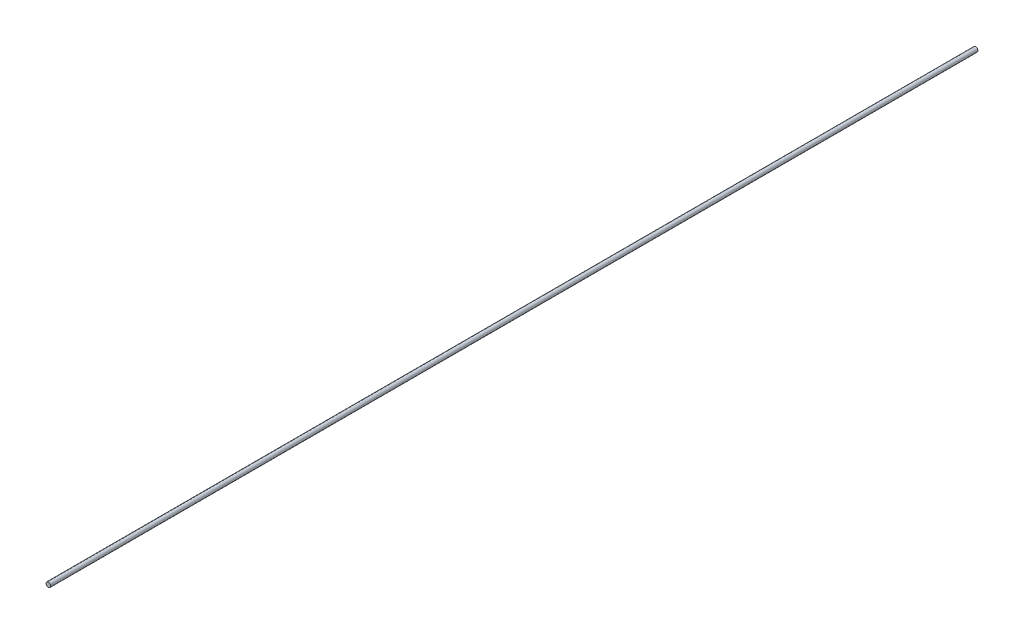
SolidWorks part; units mm, degrees
material "CF"
ref_plane "Front Plane" through (0, 0, 0) normal (0, 0, 1) x (1, 0, 0)
ref_plane "Top Plane" through (0, 0, 0) normal (0, 1, 0) x (1, 0, 0)
ref_plane "Right Plane" through (0, 0, 0) normal (1, 0, 0) x (0, 0, -1)
sketch "Sketch1" plane through (0, 0, 0) normal (0, 0, 1) x (1, 0, 0)
  circle A0 centre (0, 0) radius 5
  dimension "D1" = 10
extrude "Boss-Extrude1" add sketch "Sketch1" along normal blind 1000.467
mirror "Mirror1" about plane through (0, 0, 0) normal (0, 0, 1) of bodies 101
